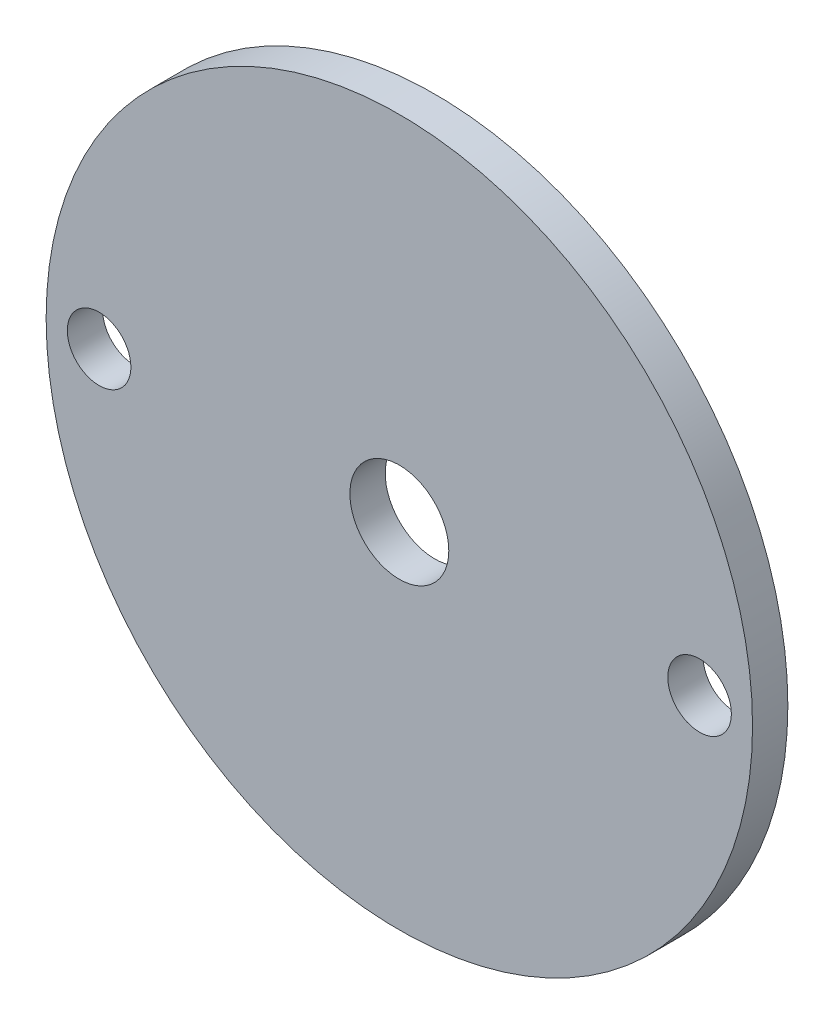
SolidWorks part; units mm, degrees
material "ASTM A36 Steel"
ref_plane "Front Plane" through (0, 0, 0) normal (0, 0, 1) x (1, 0, 0)
ref_plane "Top Plane" through (0, 0, 0) normal (0, 1, 0) x (1, 0, 0)
ref_plane "Right Plane" through (0, 0, 0) normal (1, 0, 0) x (0, 0, -1)
sketch "Sketch1" plane through (0, 0, 0) normal (0, 0, 1) x (1, 0, 0)
  circle A0 centre (0, 0) radius 50
  circle A1 centre (0, 0) radius 7
  dimension "D1" = 100
  dimension "D2" = 14
extrude "Boss-Extrude1" add sketch "Sketch1" along normal blind 5
sketch "Sketch2" plane through (0, 0, 5) normal (0, 0, 1) x (1, 0, 0)
  circle A1 centre (-42.5, 0) radius 4.5
  circle A2 centre (42.5, 0) radius 4.5
  dimension "D1" = 9
  dimension "D2" = 9
extrude "Cut-Extrude1" cut sketch "Sketch2" against normal blind 5
